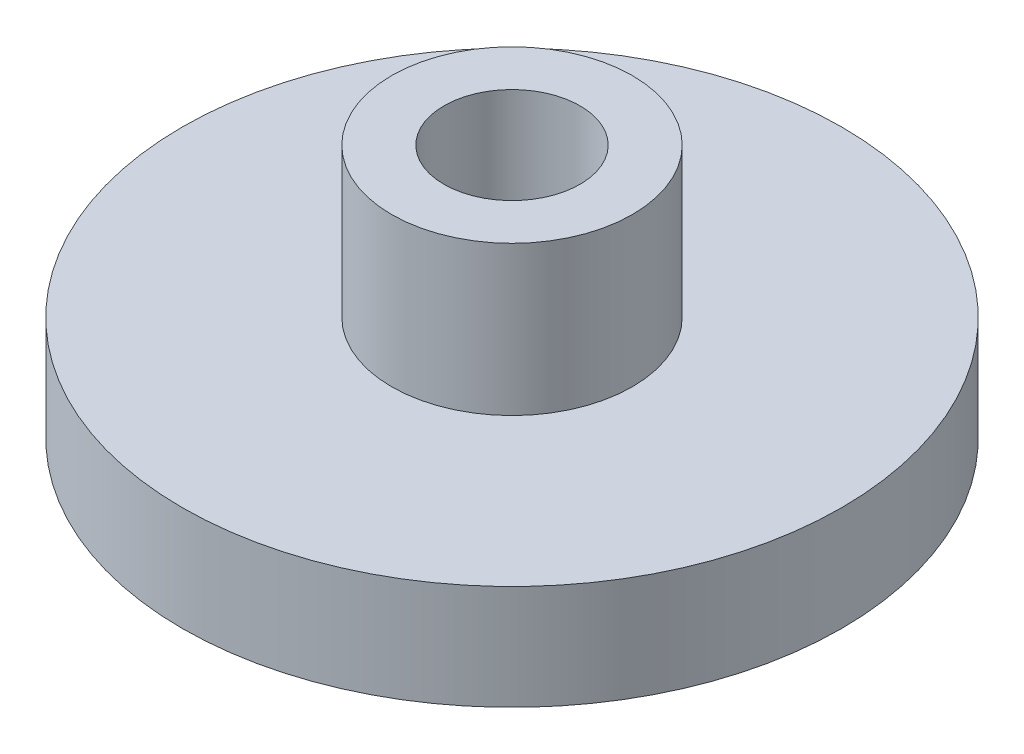
SolidWorks part; units mm, degrees
ref_plane "Front Plane" through (0, 0, 0) normal (0, 0, 1) x (1, 0, 0)
ref_plane "Top Plane" through (0, 0, 0) normal (0, 1, 0) x (1, 0, 0)
ref_plane "Right Plane" through (0, 0, 0) normal (1, 0, 0) x (0, 0, -1)
sketch "Sketch2" plane through (0, 0, 0) normal (0, 0, 1) x (1, 0, 0)
  line L0 (8.255, 0) -> (8.255, 30.8)
  line L1 (55, 0) -> (-55, 0) construction
  line L2 (8.255, 30.8) -> (14.605, 30.8)
  line L3 (14.605, 30.8) -> (14.605, 12.7)
  line L4 (14.605, 12.7) -> (40.005, 12.7)
  line L5 (40.005, 12.7) -> (40.005, 0)
  line L6 (40.005, 0) -> (8.255, 0)
  line L7 (0, -55) -> (0, 55) construction
  line L8 (0, 47.9159) -> (0, -9.2249) construction
  dimension "D1" = 30.8
  dimension "D2" = 12.7
  dimension "D3" = 8.255
  dimension "D4" = 25.4
  dimension "D5" = 6.35
revolve "Revolve1" add sketch "Sketch2" angle 360 about L8
